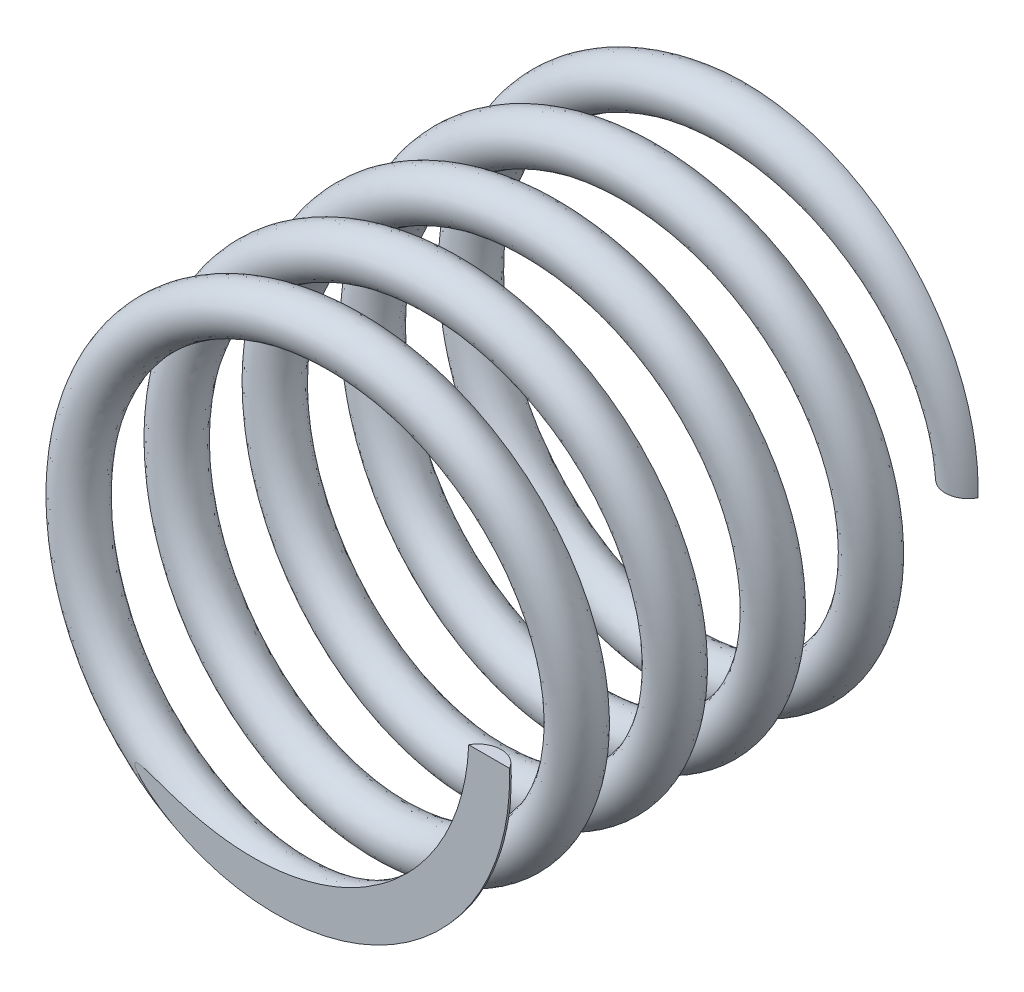
SolidWorks part; units mm, degrees
material "AISI 1020"
ref_plane "Front" through (0, 0, 0) normal (0, 0, 1) x (1, 0, 0)
ref_plane "Top" through (0, 0, 0) normal (0, 1, 0) x (1, 0, 0)
ref_plane "Right" through (0, 0, 0) normal (1, 0, 0) x (0, 0, -1)
sketch "Sketch1" plane through (0, 0, 0) normal (0, 0, 1) x (1, 0, 0)
  circle A0 centre (0, 0) radius 29
  dimension "D1" = 58
curve "Helix/Spiral1" pitch 12.7 height 63.5 turns 5
sketch "Sketch2" plane through (0, 0, 0) normal (0, 1, 0) x (1, 0, 0)
  circle A0 centre (29, 0) radius 3
  spline S0 degree 3 poles (29, 0) (29, -0.1774) (28.3224, -0.5339) (25.3434, -1.0672) (20.6083, -1.6009) (14.4453, -2.1344) (7.2813, -2.6681) (-0.3873, -3.2017) (-8.029, -3.7353) (-15.1143, -4.2689) (-21.1524, -4.8025) (-25.7247, -5.3361) (-28.5146, -5.8697) (-29.3286, -6.4034) (-28.1104, -6.937) (-24.9444, -7.4706) (-20.0499, -8.0042) (-13.7661, -8.5378) (-6.5285, -9.0714) (1.1615, -9.605) (8.771, -10.1387) (15.7728, -10.6723) (21.6817, -11.2059) (26.0881, -11.7395) (28.6869, -12.2731) (29.2979, -12.8067) (27.8788, -13.3403) (24.528, -13.8739) (19.4775, -14.4076) (13.0774, -14.9412) (5.7712, -15.4748) (-1.935, -16.0084) (-9.507, -16.542) (-16.4203, -17.0756) (-22.1958, -17.6092) (-26.4334, -18.1429) (-28.8393, -18.6765) (-29.2469, -19.2101) (-27.6279, -19.7437) (-24.0945, -20.2773) (-18.8916, -20.8109) (-12.3796, -21.3445) (-5.0099, -21.8782) (2.707, -22.4118) (10.2364, -22.9454) (17.0564, -23.479) (22.6946, -24.0126) (26.7602, -24.5462) (28.9715, -25.0798) (29.1754, -25.6134) (27.3576, -26.1471) (23.6442, -26.6807) (18.2925, -27.2143) (11.6732, -27.7479) (4.245, -28.2815) (-3.4773, -28.8151) (-10.9586, -29.3487) (-17.6806, -29.8824) (-23.1775, -30.416) (-27.0683, -30.9496) (-29.0836, -31.4832) (-29.0836, -32.0168) (-27.0683, -32.5504) (-23.1775, -33.084) (-17.6806, -33.6176) (-10.9586, -34.1513) (-3.4773, -34.6849) (4.245, -35.2185) (11.6732, -35.7521) (18.2925, -36.2857) (23.6442, -36.8193) (27.3576, -37.3529) (29.1754, -37.8866) (28.9715, -38.4202) (26.7602, -38.9538) (22.6946, -39.4874) (17.0564, -40.021) (10.2364, -40.5546) (2.707, -41.0882) (-5.0099, -41.6218) (-12.3796, -42.1555) (-18.8916, -42.6891) (-24.0945, -43.2227) (-27.6279, -43.7563) (-29.2469, -44.2899) (-28.8393, -44.8235) (-26.4334, -45.3571) (-22.1958, -45.8908) (-16.4203, -46.4244) (-9.507, -46.958) (-1.935, -47.4916) (5.7712, -48.0252) (13.0774, -48.5588) (19.4775, -49.0924) (24.528, -49.6261) (27.8788, -50.1597) (29.2979, -50.6933) (28.6869, -51.2269) (26.0881, -51.7605) (21.6817, -52.2941) (15.7728, -52.8277) (8.771, -53.3613) (1.1615, -53.895) (-6.5285, -54.4286) (-13.7661, -54.9622) (-20.0499, -55.4958) (-24.9444, -56.0294) (-28.1104, -56.563) (-29.3286, -57.0966) (-28.5146, -57.6303) (-25.7247, -58.1639) (-21.1524, -58.6975) (-15.1143, -59.2311) (-8.029, -59.7647) (-0.3873, -60.2983) (7.2813, -60.8319) (14.4453, -61.3656) (20.6083, -61.8991) (25.3434, -62.4328) (28.3224, -62.9661) (29, -63.3226) (29, -63.5) knots 0 0 0 0 0.008403 0.016807 0.02521 0.033613 0.042017 0.05042 0.058824 0.067227 0.07563 0.084034 0.092437 0.10084 0.109244 0.117647 0.12605 0.134454 0.142857 0.151261 0.159664 0.168067 0.176471 0.184874 0.193277 0.201681 0.210084 0.218487 0.226891 0.235294 0.243697 0.252101 0.260504 0.268908 0.277311 0.285714 0.294118 0.302521 0.310924 0.319328 0.327731 0.336134 0.344538 0.352941 0.361345 0.369748 0.378151 0.386555 0.394958 0.403361 0.411765 0.420168 0.428571 0.436975 0.445378 0.453782 0.462185 0.470588 0.478992 0.487395 0.495798 0.504202 0.512605 0.521008 0.529412 0.537815 0.546218 0.554622 0.563025 0.571429 0.579832 0.588235 0.596639 0.605042 0.613445 0.621849 0.630252 0.638655 0.647059 0.655462 0.663866 0.672269 0.680672 0.689076 0.697479 0.705882 0.714286 0.722689 0.731092 0.739496 0.747899 0.756303 0.764706 0.773109 0.781513 0.789916 0.798319 0.806723 0.815126 0.823529 0.831933 0.840336 0.848739 0.857143 0.865546 0.87395 0.882353 0.890756 0.89916 0.907563 0.915966 0.92437 0.932773 0.941176 0.94958 0.957983 0.966387 0.97479 0.983193 0.991597 1 1 1 1 construction
  dimension "D1" = 6
sweep "Sweep1" add profiles "Sketch2" path "Helix/Spiral1"
sketch "Sketch3" plane through (0, 0, 0) normal (0, 1, 0) x (1, 0, 0)
  line L0 (0, -1.4169) -> (0, -62.0733)
ref_plane "Plane1" through (0, 0, 1.4169) normal (0, 0, 1) x (1, 0, 0)
other "SurfaceCut1"
ref_plane "Plane3" through (0, 0, 62.0733) normal (0, 0, -1) x (-1, 0, 0)
other "SurfaceCut4"
